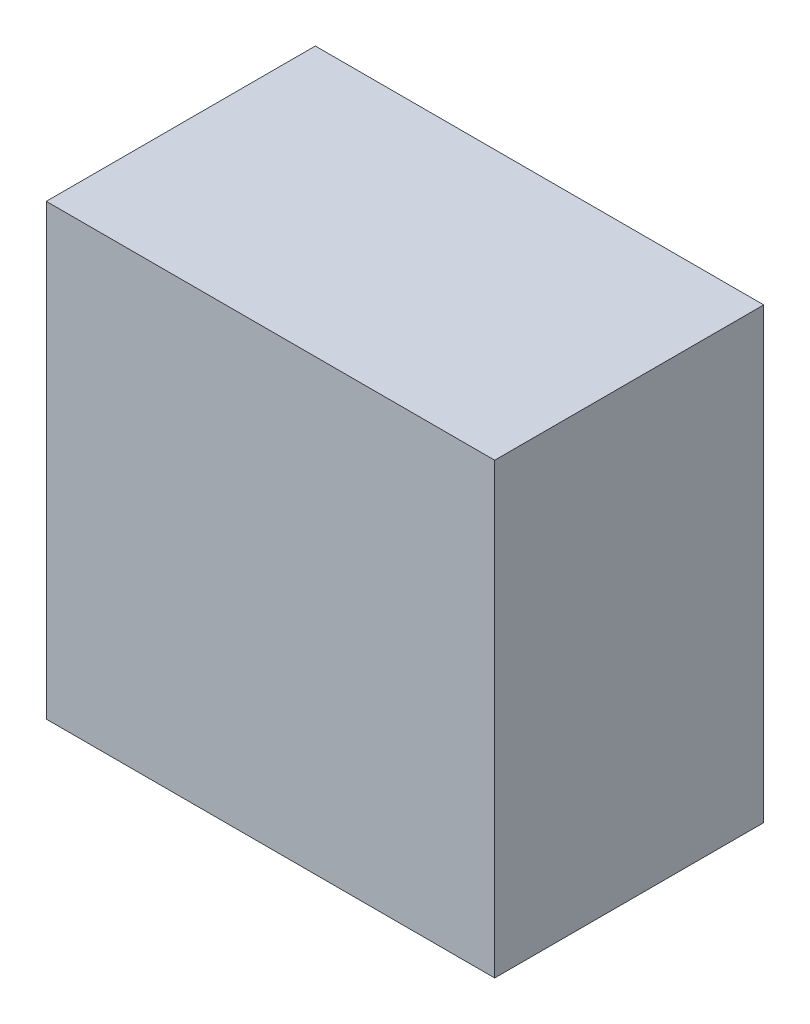
SolidWorks part; units mm, degrees
ref_plane "Front Plane" through (0, 0, 0) normal (0, 0, 1) x (1, 0, 0)
ref_plane "Top Plane" through (0, 0, 0) normal (0, 1, 0) x (1, 0, 0)
ref_plane "Right Plane" through (0, 0, 0) normal (1, 0, 0) x (0, 0, -1)
sketch "Sketch1" plane through (0, 0, 0) normal (0, 0, 1) x (1, 0, 0)
  line L1 (-37.5, 37.5) -> (37.5, 37.5)
  line L2 (-37.5, 37.5) -> (-37.5, -37.5)
  line L3 (-37.5, -37.5) -> (37.5, -37.5)
  line L4 (37.5, 37.5) -> (37.5, -37.5)
  line L5 (-37.5, 37.5) -> (37.5, -37.5) construction
  line L6 (-37.5, -37.5) -> (37.5, 37.5) construction
  point P0 (0, 0)
  dimension "D1" = 75
extrude "Boss-Extrude1" add sketch "Sketch1" along normal mid plane 45
